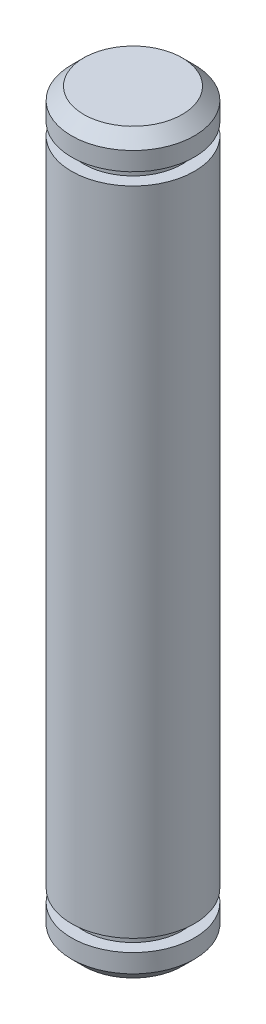
SolidWorks part; units mm, degrees
ref_plane "Front Plane" through (0, 0, 0) normal (0, 0, 1) x (1, 0, 0)
ref_plane "Top Plane" through (0, 0, 0) normal (0, 1, 0) x (1, 0, 0)
ref_plane "Right Plane" through (0, 0, 0) normal (1, 0, 0) x (0, 0, -1)
sketch "Sketch1" plane through (0, 0, 0) normal (0, 1, 0) x (1, 0, 0)
  circle A0 centre (0, 0) radius 5
  dimension "D1" = 10
extrude "Boss-Extrude1" add sketch "Sketch1" along normal blind 60
chamfer "Chamfer1" distance 1 angle 45 2 edges at (0, 0, 5) (0, 60, 5)
sketch "Sketch2" plane through (0, 0, 0) normal (0, -1, 0) x (1, 0, 0)
  circle A0 centre (0, 0) radius 4
  circle A1 centre (0, 0) radius 7.5
  dimension "D1" = 15
  dimension "D2" = 8
extrude "Cut-Extrude1" cut sketch "Sketch2" against normal blind 1 from offset 2.5 offset against normal yes
sketch "Sketch3" plane through (0, 60, 0) normal (0, 1, 0) x (1, 0, 0)
  circle A0 centre (0, 0) radius 4
  circle A1 centre (0, 0) radius 7.5
  dimension "D1" = 15
  dimension "D2" = 8
extrude "Cut-Extrude2" cut sketch "Sketch3" against normal blind 1 from offset 2.5 offset against normal yes
